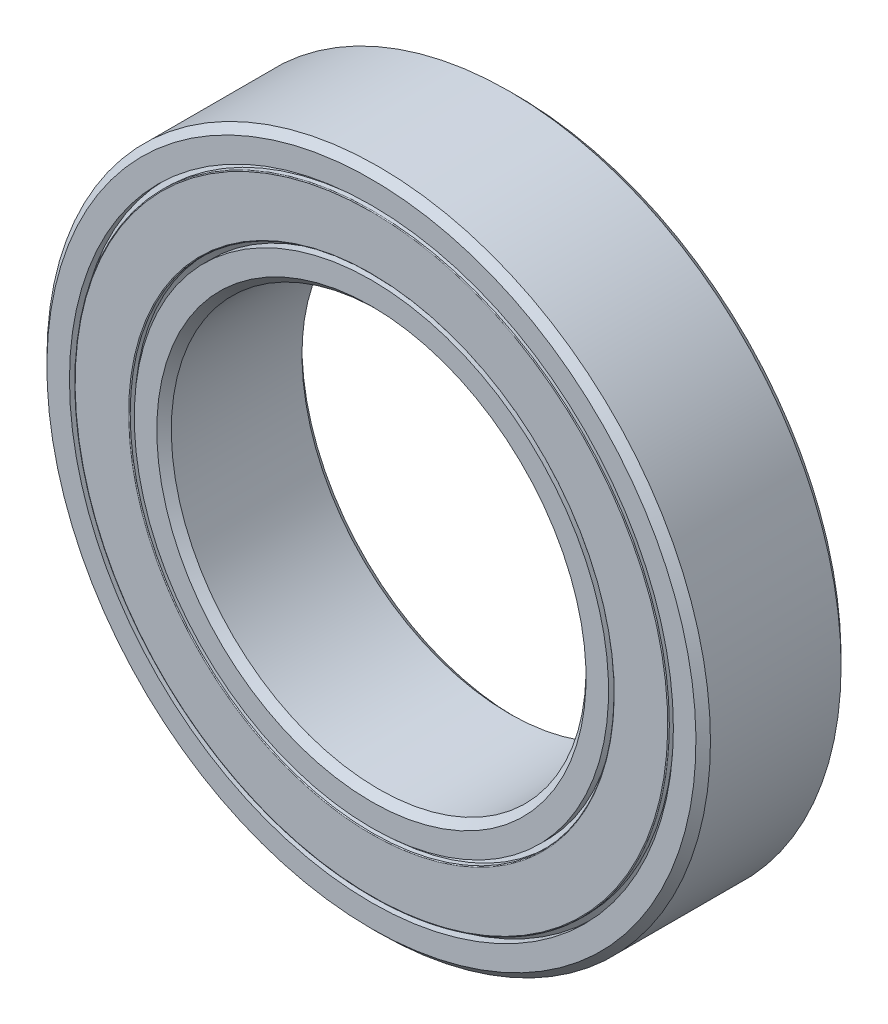
SolidWorks part; units mm, degrees
ref_plane "Front Plane" through (0, 0, 0) normal (0, 0, 1) x (1, 0, 0)
ref_plane "Top Plane" through (0, 0, 0) normal (0, 1, 0) x (1, 0, 0)
ref_plane "Right Plane" through (0, 0, 0) normal (1, 0, 0) x (0, 0, -1)
sketch "Sketch1" plane through (0, 0, 0) normal (0, 0, 1) x (1, 0, 0)
  line L0 (-16, 0) -> (16, 0) construction
  line L1 (-10, 0) -> (10, 0) construction
  circle A0 centre (0, 0) radius 10 construction
  circle A1 centre (0, 0) radius 16 construction
  point P3 (0, 0)
  point P6 (0, 0)
  point P7 (0, -10)
  point P11 (0, -16)
  point P12 (0, 10)
  point P13 (0, 16)
  dimension "OD" = 32
  dimension "ID" = 20
sketch "Sketch2" plane through (0, 0, 0) normal (1, 0, 0) x (0, 0, -1)
  line L0 (-3.5, 16) -> (3.5, 16) construction
  line L1 (0, 16) -> (0, -16) construction
  line L2 (3.15, 16) -> (-3.15, 16)
  line L3 (-3.15, 16) -> (-3.5, 15.65)
  line L4 (-3.5, 15.65) -> (-3.5, 14.5625)
  line L5 (-3.5, 14.5625) -> (-1.5556, 14.5625)
  line L6 (3.5, 14.5625) -> (1.5556, 14.5625)
  line L7 (3.5, 15.65) -> (3.5, 14.5625)
  line L8 (3.15, 16) -> (3.5, 15.65)
  line L9 (0, 16) -> (0, 13) construction
  line L10 (0, 13) -> (0, 10) construction
  line L11 (0, 16) -> (0, -16) construction
  line L12 (-3.5, 0) -> (3.5, 0) construction
  line L13 (3.5, 10) -> (-3.5, 10) construction
  line L14 (0, 15.2048) -> (0, 10.7952) construction
  line L15 (-3.5, -10) -> (3.5, -10) construction
  line L16 (-3.5, 10) -> (-3.5, -10) construction
  line L17 (3.5, 16) -> (3.5, -16) construction
  line L18 (-3.5, 14.5625) -> (-3.5, 14.4063) construction
  line L19 (-3.5, 14.4063) -> (-3.5, 14.25) construction
  line L20 (-3.5, 14.25) -> (-3.5, 14.0938) construction
  line L21 (-3.5, 14.0938) -> (-3.5, 13.9375) construction
  line L22 (-3.5, 13.9375) -> (-3.5, 13.7813) construction
  line L24 (-2.5278, 14.5625) -> (-2.5278, 13) construction
  arc A0 (-1.5556, 14.5625) -> (1.5556, 14.5625) centre (0, 13) cw
  circle A1 centre (0, 13) radius 2.2048 construction
  point P14 (0, 10)
  point P17 (0, 0)
  point P21 (0, 16)
  point P29 (0, 10)
  point P30 (0, -10)
  point P46 (-2.5278, 13.7813)
  dimension "Width" = 7
  dimension "D1" = 45
  dimension "D2" = 0.35
  dimension "D3" = 3.1111
  dimension "D4" = 1.5625
  dimension "For Shaft Diameter" = 20
  dimension "For Housing ID" = 32
sketch "Sketch3" plane through (0, 0, 0) normal (1, 0, 0) x (0, 0, -1)
  line L0 (3.15, 16) -> (3.5, 15.65) construction
  line L1 (3.5, 15.65) -> (3.5, 14.5625) construction
  line L2 (3.5, 14.5625) -> (1.5556, 14.5625) construction
  line L3 (-3.5, 14.5625) -> (-1.5556, 14.5625) construction
  line L4 (-3.5, 15.65) -> (-3.5, 14.5625) construction
  line L5 (-3.15, 16) -> (-3.5, 15.65) construction
  line L6 (3.15, 16) -> (-3.15, 16) construction
  line L7 (3.15, 16) -> (3.5, 15.65)
  line L8 (3.5, 15.65) -> (3.5, 14.5625)
  line L9 (3.5, 14.5625) -> (1.5556, 14.5625)
  line L10 (-3.5, 14.5625) -> (-1.5556, 14.5625)
  line L11 (-3.5, 15.65) -> (-3.5, 14.5625)
  line L12 (-3.15, 16) -> (-3.5, 15.65)
  line L13 (3.15, 16) -> (-3.15, 16)
  arc A0 (1.5556, 14.5625) -> (-1.5556, 14.5625) centre (0, 13) ccw construction
  arc A1 (1.5556, 14.5625) -> (-1.5556, 14.5625) centre (0, 13) ccw
revolve "Revolve1" add sketch "Sketch3" angle 360 about L12
sketch "Sketch4" plane through (0, 0, 0) normal (1, 0, 0) x (0, 0, -1)
  line L0 (0, 16) -> (0, -16) construction
  line L1 (0, 16) -> (0, -16) construction
  line L2 (-3.15, 10) -> (-3.5, 10.35)
  line L3 (-3.5, 10.35) -> (-3.5, 11.4375)
  line L5 (-3.5, 11.4375) -> (-1.5556, 11.4375)
  line L6 (-3.15, 10) -> (3.15, 10)
  line L8 (3.15, 10) -> (3.5, 10.35)
  line L10 (3.5, 10.35) -> (3.5, 11.4375)
  line L11 (3.5, 11.4375) -> (1.5556, 11.4375)
  line L12 (-3.5, 15.65) -> (-3.5, 14.5625) construction
  line L13 (3.15, 16) -> (3.5, 15.65) construction
  line L15 (3.5, -15.65) -> (3.5, 15.65) construction
  line L16 (3.15, 16) -> (3.15, -16) construction
  arc A1 (1.5556, 11.4375) -> (-1.5556, 11.4375) centre (0, 13) cw
  circle A2 centre (0, 13) radius 2.2048 construction
  point P1 (0, 10)
revolve "Revolve2" add sketch "Sketch4" angle 360 about L12
sketch "Sketch5" plane through (0, 0, 0) normal (1, 0, 0) x (0, 0, -1)
  line L0 (-2.2048, 13) -> (2.2048, 13)
  arc A2 (-2.2048, 13) -> (2.2048, 13) centre (0, 13) cw
  arc A3 (1.5556, 14.5625) -> (-1.5556, 14.5625) centre (0, 13) ccw construction
revolve "Revolve3" add sketch "Sketch5" angle 360 about L0
sketch "Sketch6" plane through (0, 0, 0) normal (1, 0, 0) x (0, 0, -1)
  line L0 (-3.5, 14.5625) -> (-3.5, 13.7812) construction
  line L1 (-3.5, 15.65) -> (-3.5, -15.65) construction
  line L2 (-3.5, 13.7812) -> (-3.5, 13) construction
  line L3 (-3.5, 13) -> (-3.5, 12.2187) construction
  line L4 (-3.5, 12.2187) -> (-3.5, 11.4375) construction
  line L5 (-3.5, 13.7812) -> (-3.2603, 13.7812) construction
  line L7 (-2.0617, 13.7812) -> (-2.0617, 12.2188) construction
  line L8 (-3.2603, 13.7812) -> (-3.0206, 13.7813) construction
  line L10 (0, 16) -> (0, -16) construction
  line L11 (0, 16) -> (0, -16) construction
  line L12 (-3.0206, 13.7813) -> (-2.7809, 13.7812) construction
  line L13 (-2.7809, 13.7812) -> (-2.5412, 13.7812) construction
  line L14 (-2.5412, 13.7812) -> (-2.3015, 13.7812) construction
  line L15 (-2.3015, 13.7812) -> (-2.0617, 13.7812) construction
  line L16 (-2.0617, 13.7812) -> (-2.3015, 13.7812)
  line L17 (-2.3015, 12.2188) -> (-2.5412, 12.2188) construction
  line L18 (-2.3015, 12.2188) -> (-2.0617, 12.2188)
  line L19 (-2.5412, 12.2188) -> (-2.5412, 13.7812) construction
  line L20 (-2.4213, 13.7812) -> (-2.4213, 12.2188) construction
  circle A0 centre (0, 13) radius 2.2048 construction
  circle A1 centre (0, 13) radius 2.2048 construction
  arc A2 (-2.3015, 13.7812) -> (-2.3015, 12.2188) centre (0.1848, 13) ccw
  arc A3 (-2.0617, 13.7812) -> (-2.0617, 12.2188) centre (0, 13) ccw
  point P28 (-2.4213, 13)
revolve "Revolve4" add sketch "Sketch6" angle 360 about L11
pattern_circular "CirPattern1" count 13 over 360 about axis through (0, 0, 0) along (0, 0, 1) of bodies 134 104
sketch "Sketch7" plane through (0, 0, 0) normal (0, 0, 1) x (1, 0, 0)
  line L0 (0, 11.4375) -> (0, 11.9583) construction
  line L1 (0, 10.7952) -> (0, 15.2048) construction
  line L2 (0, 11.9583) -> (0, 12.4792) construction
  line L3 (0, 12.4792) -> (0, 13) construction
  line L4 (0, 13) -> (0, 13.5208) construction
  line L5 (0, 13.5208) -> (0, 14.0417) construction
  line L6 (0, 14.0417) -> (0, 14.5625) construction
  line L7 (0, 15.65) -> (0, 14.5625) construction
  line L8 (0, 16) -> (0, -16) construction
  circle A0 centre (0, 0) radius 11.4375 construction
  circle A1 centre (0, 0) radius 13
  circle A2 centre (0, 0) radius 13.7813
  point P19 (0, 13.7813)
extrude "Boss-Extrude1" add sketch "Sketch7" along normal mid plane 1.1667 separate body
sketch "Sketch8" plane through (0, 0, 0) normal (1, 0, 0) x (0, 0, -1)
  line L0 (-3.5, 14.4063) -> (-3.5, 14.25) construction
  line L1 (-3.5, 14.3281) -> (-3.2407, 14.3281)
  line L2 (-3.5, 14.3281) -> (-3.5, 11.6719)
  line L3 (-3.5, 11.6719) -> (-3.2407, 11.6719)
  line L4 (-3.1111, 14.3281) -> (-3.1111, 11.6719)
  line L5 (0, 16) -> (0, 13) construction
  line L10 (-3.2407, 14.3281) -> (-3.1111, 14.5625)
  line L11 (-3.5, 14.5625) -> (-1.5556, 14.5625) construction
  line L12 (-3.1111, 14.5625) -> (-3.1111, 14.3281)
  line L13 (-3.2407, 11.6719) -> (-3.1111, 11.4375)
  line L14 (-3.1111, 11.4375) -> (-3.1111, 11.6719)
  line L15 (-3.5, 14.5625) -> (-3.3704, 14.5625) construction
  line L16 (3.5, 14.3281) -> (3.5, 11.6719)
  line L17 (3.5, 11.6719) -> (3.2407, 11.6719)
  line L18 (3.2407, 11.6719) -> (3.1111, 11.4375)
  line L19 (3.1111, 11.4375) -> (3.1111, 11.6719)
  line L20 (3.1111, 14.3281) -> (3.1111, 11.6719)
  line L21 (3.1111, 14.5625) -> (3.1111, 14.3281)
  line L22 (3.2407, 14.3281) -> (3.1111, 14.5625)
  line L23 (3.5, 14.3281) -> (3.2407, 14.3281)
  line L24 (-3.3704, 14.5625) -> (-3.2407, 14.5625) construction
  line L25 (-3.2407, 14.5625) -> (-3.1111, 14.5625) construction
  line L27 (-3.5, 11.4375) -> (-1.5556, 11.4375) construction
  point P23 (-3.5, 14.3281)
  dimension "D1" = 0.3889
revolve "Revolve5" add sketch "Sketch8" angle 360 about L12
fillet "Fillet1" radius 0.0389 2 edges at (0, -14.3281, 3.5) (0, -11.6719, 3.5)
fillet "Fillet2" radius 0.0389 2 edges at (0, -11.6719, -3.5) (0, -14.3281, -3.5)
equation "\"D2@Sketch2\" = \"Width@Sketch2\" * .05"
equation "\"D3@Sketch2\" = \"Width@Sketch2\" / 2.25"
equation "\"D4@Sketch2\"=( \"OD@Sketch1\" - \"Width@Sketch2\" )  *.5*.125"
equation "\"D1@Boss-Extrude1\" = \"Width@Sketch2\" / 6"
equation "\"D1@Sketch8\"=(\"Width@Sketch2\"-\"D3@Sketch2\")*.5*.2"
equation "\"D1@Fillet1\"=\"d1@sketch8\"*.1"
equation "\"D1@Fillet2\"=\"d1@fillet1\""
